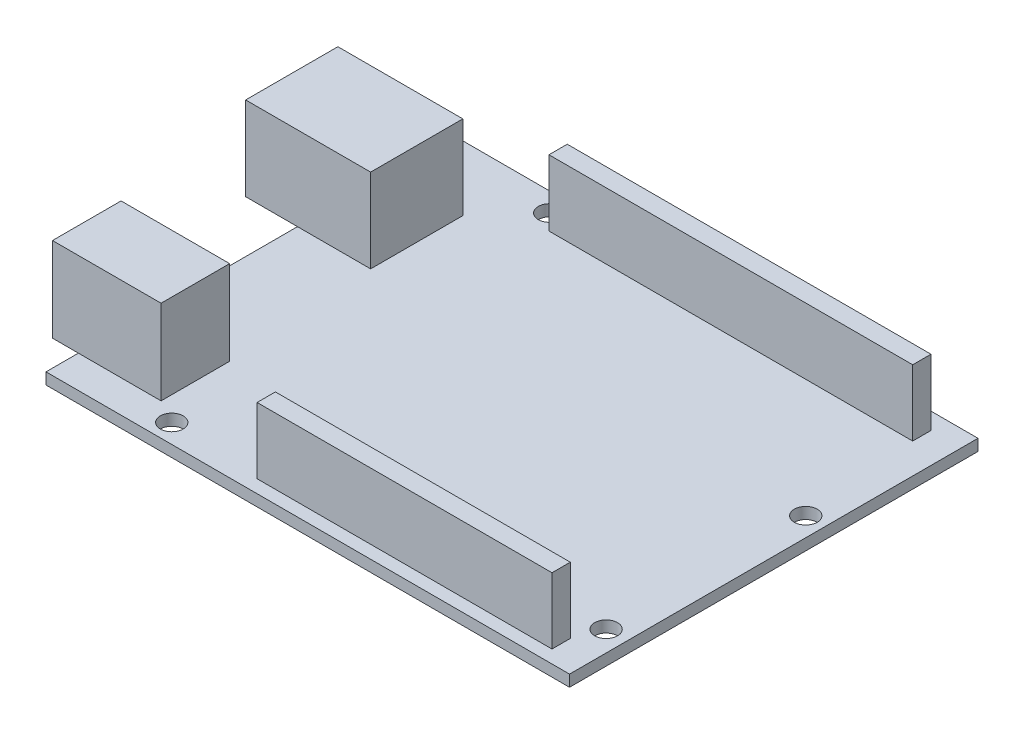
SolidWorks part; units mm, degrees
ref_plane "Front Plane" through (0, 0, 0) normal (0, 0, 1) x (1, 0, 0)
ref_plane "Top Plane" through (0, 0, 0) normal (0, 1, 0) x (1, 0, 0)
ref_plane "Right Plane" through (0, 0, 0) normal (1, 0, 0) x (0, 0, -1)
ref_plane "PCB_TOP" through (0, 1.5, 0) normal (0, 1, 0) x (1, 0, 0)
sketch "Sketch2" plane through (0, 0, 0) normal (0, 1, 0) x (1, 0, 0)
  line L1 (0, 0) -> (68.7, 0)
  line L2 (0, 0) -> (0, 53.6)
  line L3 (0, 53.6) -> (68.7, 53.6)
  line L4 (68.7, 0) -> (68.7, 53.6)
  dimension "D1" = 68.7
  dimension "D2" = 53.6
extrude "PCB" add sketch "Sketch2" along normal up to surface (1.5 mm away) up to plane "PCB_TOP"
sketch "Sketch3" plane through (0, 0, 0) normal (0, 1, 0) x (1, 0, 0)
  line L1 (-3.4, 13.25) -> (10.85, 13.25)
  line L2 (-3.4, 13.25) -> (-3.4, 4.25)
  line L3 (-3.4, 4.25) -> (10.85, 4.25)
  line L4 (10.85, 13.25) -> (10.85, 4.25)
  dimension "D1" = 14.25
  dimension "D2" = 9
  dimension "D3" = 4.25
  dimension "D4" = 3.4
extrude "Barrel Jack" add sketch "Sketch3" along normal blind 11.1 from surface at 1.5 starting at plane "PCB_TOP"
sketch "Sketch4" plane through (0, 0, 0) normal (0, 1, 0) x (1, 0, 0)
  line L1 (-6.8, 33) -> (9.6, 33)
  line L2 (-6.8, 33) -> (-6.8, 45.1)
  line L3 (-6.8, 45.1) -> (9.6, 45.1)
  line L4 (9.6, 33) -> (9.6, 45.1)
  dimension "D1" = 16.4
  dimension "D2" = 12.1
  dimension "D3" = 33
  dimension "D4" = 6.8
extrude "HWSerial Port" add sketch "Sketch4" along normal blind 11 from surface at 1.5 starting at plane "PCB_TOP"
sketch "Sketch5" plane through (0, 0, 0) normal (0, 1, 0) x (1, 0, 0)
  line L1 (17, 51.4) -> (64.73, 51.4)
  line L2 (17, 51.4) -> (17, 49)
  line L3 (17, 49) -> (64.73, 49)
  line L4 (64.73, 51.4) -> (64.73, 49)
  line L5 (26, 4.1) -> (64.7, 4.1)
  line L6 (26, 4.1) -> (26, 1.7)
  line L7 (26, 1.7) -> (64.7, 1.7)
  line L8 (64.7, 4.1) -> (64.7, 1.7)
  dimension "D1" = 2.4
  dimension "D2" = 38.7
  dimension "D3" = 47.73
  dimension "D4" = 17
  dimension "D5" = 26
  dimension "D6" = 49
  dimension "D7" = 1.7
extrude "Boss-Extrude4" add sketch "Sketch5" along normal blind 8.67 from surface at 1.5 starting at plane "PCB_TOP"
sketch "Sketch6" plane through (0, 1.5, 0) normal (0, 1, 0) x (1, 0, 0)
  line L1 (68.7, 0) -> (68.7, 53.6) construction
  point P0 (14, 2.5)
  point P1 (66, 7.5)
  point P2 (15, 51.1)
  point P3 (66.2, 33.5)
  dimension "D1" = 14
  dimension "D2" = 2.5
  dimension "D3" = 66
  dimension "D4" = 7.5
  dimension "D5" = 2.5
  dimension "D6" = 15
  dimension "D7" = 33.5
  dimension "D8" = 2.5
hole_wizard "Ø3.0mm Dowel Hole1" positions "Sketch8" profile "Sketch9" hole size "Ø3.0" standard "ANSI Metric"
sketch "Sketch8" plane through (0, 1.5, 0) normal (0, 1, 0) x (1, 0, 0)
  point P0 (15, 51.1)
  point P3 (14, 2.5)
  point P6 (66, 7.5)
  point P10 (66.2, 33.5)
sketch "Sketch9" plane through (15, 1.5, -51.1) normal (1, 0, 0) x (0, 0, 1)
  line L0 (0, 0) -> (0, 8.4013)
  line L1 (0, 8.4013) -> (1.5, 7.5)
  line L2 (1.5, 7.5) -> (1.5, 0)
  line L5 (1.5, 0) -> (0, 0)
  line L10 (0, 8.4013) -> (-1.5, 7.5) construction
  line L11 (0, -6.35) -> (0, 107.95) construction
  dimension "Hole Dia." = 3
  dimension "Hole Depth" = 7.5
  dimension "Drill Angle" = 118
